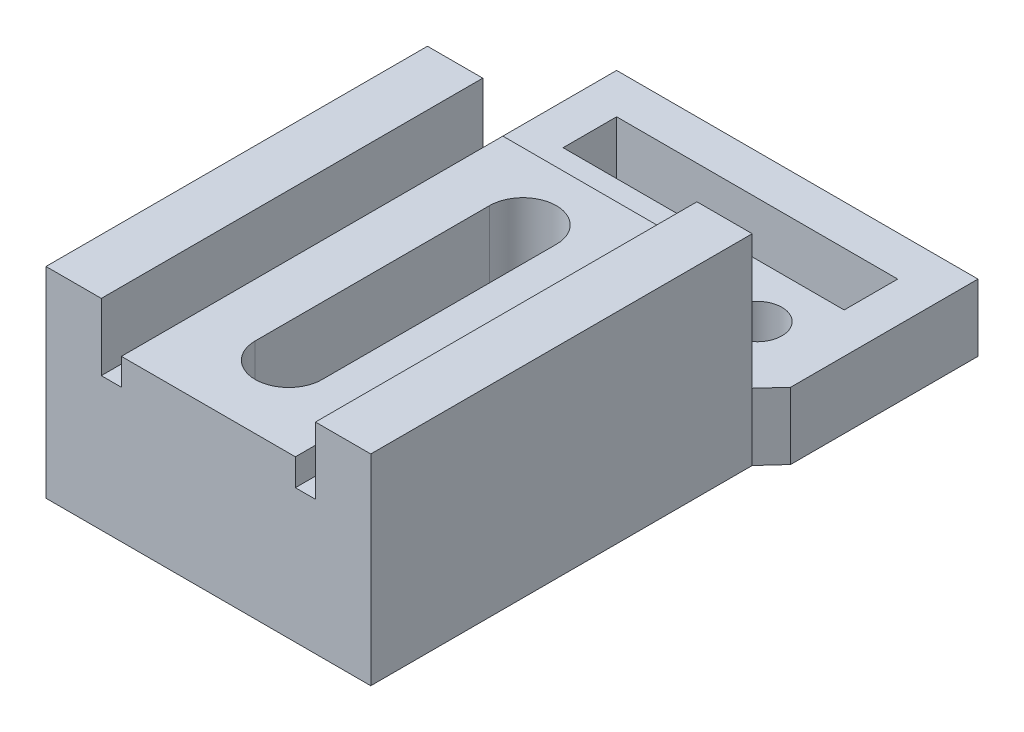
SolidWorks part; units mm, degrees
ref_plane "Alzado" through (0, 0, 0) normal (0, 0, 1) x (1, 0, 0)
ref_plane "Planta" through (0, 0, 0) normal (0, 1, 0) x (1, 0, 0)
ref_plane "Vista lateral" through (0, 0, 0) normal (1, 0, 0) x (0, 0, -1)
sketch "Croquis1" plane through (0, 0, 0) normal (1, 0, 0) x (0, 0, -1)
  line L0 (49.6616, 6.8488) -> (49.6616, -3.1512)
  line L2 (79.6616, -3.1512) -> (79.6616, 6.8488)
  line L3 (79.6616, 6.8488) -> (49.6616, 6.8488)
  line L7 (49.6616, -3.1512) -> (79.6616, -3.1512)
  dimension "D1" = 10
  dimension "D2" = 30
extrude "Saliente-Extruir1" add sketch "Croquis1" against normal blind 18
sketch "Croquis2" plane through (0, 13.6977, -49.6616) normal (0, 0, -1) x (1, 0, 0)
  line L0 (-17, 9.8488) -> (-17, 6.8488)
  line L1 (-17, 6.8488) -> (-1, 6.8488)
  line L2 (-1, 6.8488) -> (-1, 9.8488)
  line L3 (-1, 9.8488) -> (-17, 9.8488)
  line L7 (-18, 6.8488) -> (0, 6.8488) construction
  dimension "D1" = 3
  dimension "D2" = 16
extrude "Cortar-Extruir1" cut sketch "Croquis2" along normal through all
hole_wizard "Diámetro de taladro Ø5.0 (5)1" positions "Croquis4" profile "Croquis3" hole size "Ø5.0" standard "Ansi Metric" end condition through all
sketch "Croquis4" plane through (0, 3.8488, 0) normal (0, 1, 0) x (1, 0, 0)
  point P0 (-9, 65.1616)
sketch "Croquis3" plane through (-9, 3.8488, -65.1616) normal (1, 0, 0) x (0, 0, 1)
  line L0 (0, 0) -> (0, 7)
  line L1 (0, 7) -> (2.5, 7)
  line L2 (2.5, 7) -> (2.5, 0)
  line L5 (2.5, 0) -> (0, 0)
  line L11 (0, -6.35) -> (0, 7) construction
  dimension "Diámetro de taladro hasta el siguiente" = 5
  dimension "Profundidad de taladro hasta el siguiente" = 7
hole_wizard "Diámetro de taladro Ø5.0 (5)2" positions "Croquis6" profile "Croquis5" hole size "Ø5.0" standard "Ansi Metric" end condition through all
sketch "Croquis6" plane through (0, 3.8488, 0) normal (0, 1, 0) x (1, 0, 0)
  point P0 (-9, 73.1616)
sketch "Croquis5" plane through (-9, 3.8488, -73.1616) normal (1, 0, 0) x (0, 0, 1)
  line L0 (0, 0) -> (0, 7)
  line L1 (0, 7) -> (2.5, 7)
  line L2 (2.5, 7) -> (2.5, 0)
  line L5 (2.5, 0) -> (0, 0)
  line L11 (0, -6.35) -> (0, 107.95) construction
  dimension "Diámetro de taladro hasta el siguiente" = 5
  dimension "Profundidad de taladro hasta el siguiente" = 7
sketch "Croquis7" plane through (0, -3.1512, 0) normal (0, -1, 0) x (1, 0, 0)
  line L0 (-17, -82.6616) -> (-9, -82.6616) construction
  line L6 (-18, -79.6616) -> (-22.5, -79.6616) construction
  line L7 (-22.5, -79.6616) -> (-22.5, -93.6616) construction
  line L8 (-17, -82.6616) -> (-17, -93.6616) construction
  line L9 (-22.5, -93.6616) -> (4.5, -93.6616)
  line L10 (-22.5, -93.6616) -> (-22.5, -79.6616)
  line L11 (-22.5, -79.6616) -> (-18, -79.6616)
  line L12 (-9, -93.6616) -> (-9, -82.6616) construction
  line L13 (4.5, -93.6616) -> (4.5, -79.6616)
  line L15 (0, -79.6616) -> (4.5, -79.6616)
  line L19 (0, -79.6616) -> (0, -49.6616)
  line L20 (0, -49.6616) -> (-18, -49.6616)
  line L21 (-18, -49.6616) -> (-18, -79.6616)
  line L22 (-18, -79.6616) -> (0, -79.6616)
  line L23 (0, -79.6616) -> (0, -49.6616)
  line L24 (0, -49.6616) -> (-18, -49.6616)
  line L25 (-18, -49.6616) -> (-18, -78.779)
  circle A0 centre (-17, -82.6616) radius 1.85
  circle A1 centre (-1, -82.6616) radius 1.85
  circle M29 centre (-9, -73.1616) radius 2.5
  circle M30 centre (-9, -65.1616) radius 2.5
  line M31 (0, -79.6616) -> (0, -49.6616)
  line M32 (0, -49.6616) -> (-18, -49.6616)
  line M33 (-18, -49.6616) -> (-18, -79.6616)
  line M34 (-18, -79.6616) -> (0, -79.6616)
  dimension "D3" = 3.7
  dimension "D2" = 14
  dimension "D4" = 11
  dimension "D5" = 8
  dimension "D6" = 0
extrude "Saliente-Extruir2" add sketch "Croquis7" along normal blind 5 contours M34 M31 M32 M33 M30 M29 | L15 L11 L10 L9 L13 A0 A1 M34
sketch "Croquis9" plane through (0, -8.1512, 0) normal (0, -1, 0) x (-1, 0, 0)
  line L0 (19.5, 86.6616) -> (-1.5, 86.6616)
  line L4 (22.5, 93.6616) -> (22.5, 79.6616) construction
  line L5 (22.5, 93.6616) -> (-4.5, 93.6616) construction
  line L7 (-4.5, 93.6616) -> (-4.5, 79.6616) construction
  line L9 (0, 79.6616) -> (-4.5, 79.6616) construction
  line L18 (-1.5, 86.6616) -> (-1.5, 90.6616)
  line L19 (-1.5, 90.6616) -> (19.5, 90.6616)
  line L20 (19.5, 90.6616) -> (19.5, 86.6616)
  dimension "D4" = 7
  dimension "D1" = 3
  dimension "D2" = 3
  dimension "D3" = 3
extrude "Cortar-Extruir3" cut sketch "Croquis9" against normal up to next
sketch "Croquis11" plane through (0, 6.8488, 0) normal (0, 1, 0) x (1, 0, 0)
  line L16 (-21.1318, 49.6616) -> (-18, 49.6616)
  line L23 (-21.1318, 49.6616) -> (-21.1318, 78.1616)
  line L25 (-18, 78.1616) -> (-18, 49.6616)
  line L26 (-18, 49.6616) -> (-9, 49.6616) construction
  line L28 (-9, 45.4271) -> (-9, 49.6616) construction
  line L32 (-9, 79.6616) -> (-9, 78.1616) construction
  line L34 (-18, 78.1616) -> (-21.1318, 78.1616)
  line L35 (3.1318, 49.6616) -> (3.1318, 78.1616)
  line L36 (0, 78.1616) -> (3.1318, 78.1616)
  line L37 (0, 78.1616) -> (0, 49.6616)
  line L38 (3.1318, 49.6616) -> (0, 49.6616)
  dimension "D1" = 1.5
sketch "Croquis12" plane through (-18, 0, 0) normal (-1, 0, 0) x (0, 0, 1)
  line L1 (-79.6616, -3.1512) -> (-78.1616, -3.1512)
  line L2 (-79.6616, -3.1512) -> (-79.6616, 6.8488)
  line L3 (-79.6616, 6.8488) -> (-78.1616, 6.8488)
  line L4 (-78.1616, -3.1512) -> (-78.1616, 6.8488)
extrude "Cortar-Extruir4" cut sketch "Croquis12" against normal up to next
extrude "Saliente-Extruir4" add sketch "Croquis11" against normal up to surface (15 mm away) contours L16 L25 L34 L23 | L35 L36 L37 L38 up to face at (-9, -8.1512, -88.6616)
sketch "Croquis13" plane through (0, 3.8488, 0) normal (0, 1, 0) x (1, 0, 0)
  line L0 (-1, 49.6616) -> (-17, 49.6616) construction
  line L1 (-17, 78.1616) -> (-15.5, 78.1616)
  line L2 (-17, 78.1616) -> (-17, 49.6616)
  line L3 (-17, 49.6616) -> (-15.5, 49.6616)
  line L4 (-15.5, 78.1616) -> (-15.5, 49.6616)
  line L5 (-9, 78.1616) -> (-9, 76.9241) construction
  line L6 (-1, 78.1616) -> (-17, 78.1616) construction
  line L7 (-1, 49.6616) -> (-2.5, 49.6616)
  line L8 (-2.5, 78.1616) -> (-2.5, 49.6616)
  line L9 (-1, 78.1616) -> (-2.5, 78.1616)
  line L10 (-1, 78.1616) -> (-1, 49.6616)
  dimension "D1" = 1.5
extrude "Cortar-Extruir5" cut sketch "Croquis13" against normal blind 2
sketch "Croquis14" plane through (0, 3.8488, 0) normal (0, 1, 0) x (1, 0, 0)
  line L0 (-9, 73.1616) -> (-9, 55.6616) construction
  line L1 (-9, 64.4116) -> (-12.7237, 64.4116) construction
  line L2 (-6.5, 55.6616) -> (-6.5, 73.1616)
  line L3 (-11.5, 73.1616) -> (-11.5, 55.6616)
  circle A3 centre (-9, 73.1616) radius 2.5 construction
  arc A4 (-6.5, 73.1616) -> (-11.5, 73.1616) centre (-9, 73.1616) ccw
  arc A5 (-6.5, 55.6616) -> (-11.5, 55.6616) centre (-9, 55.6616) cw
  dimension "D1" = 17.5
extrude "Cortar-Extruir6" cut sketch "Croquis14" against normal up to next (12 mm away) from surface at 3 contours L2 A4 L3 A5 starting at face at (-19.0659, 6.8488, -63.9116)
sketch "Croquis15" plane through (0, -3.1512, 0) normal (0, 1, 0) x (1, 0, 0)
  line L0 (-18, 78.1616) -> (-18, 79.6616)
  line L1 (-18, 79.6616) -> (-22.5, 79.6616)
  line L2 (-17, 78.1616) -> (-21.1318, 78.1616) construction
  line L3 (-18, 78.1616) -> (-21.1318, 78.1616)
  line L4 (-21.1318, 78.1616) -> (-22.5, 79.6616)
  line L5 (-9, 78.1616) -> (-9, 79.4996) construction
  line L6 (0, 78.1616) -> (-18, 78.1616) construction
  line L7 (0, 78.1616) -> (3.1318, 78.1616)
  line L8 (0, 78.1616) -> (0, 79.6616)
  line L9 (0, 79.6616) -> (4.5, 79.6616)
  line L10 (3.1318, 78.1616) -> (4.5, 79.6616)
extrude "Saliente-Extruir5" add sketch "Croquis15" against normal up to surface (5 mm away) up to face at (-9, -8.1512, -88.6616)
